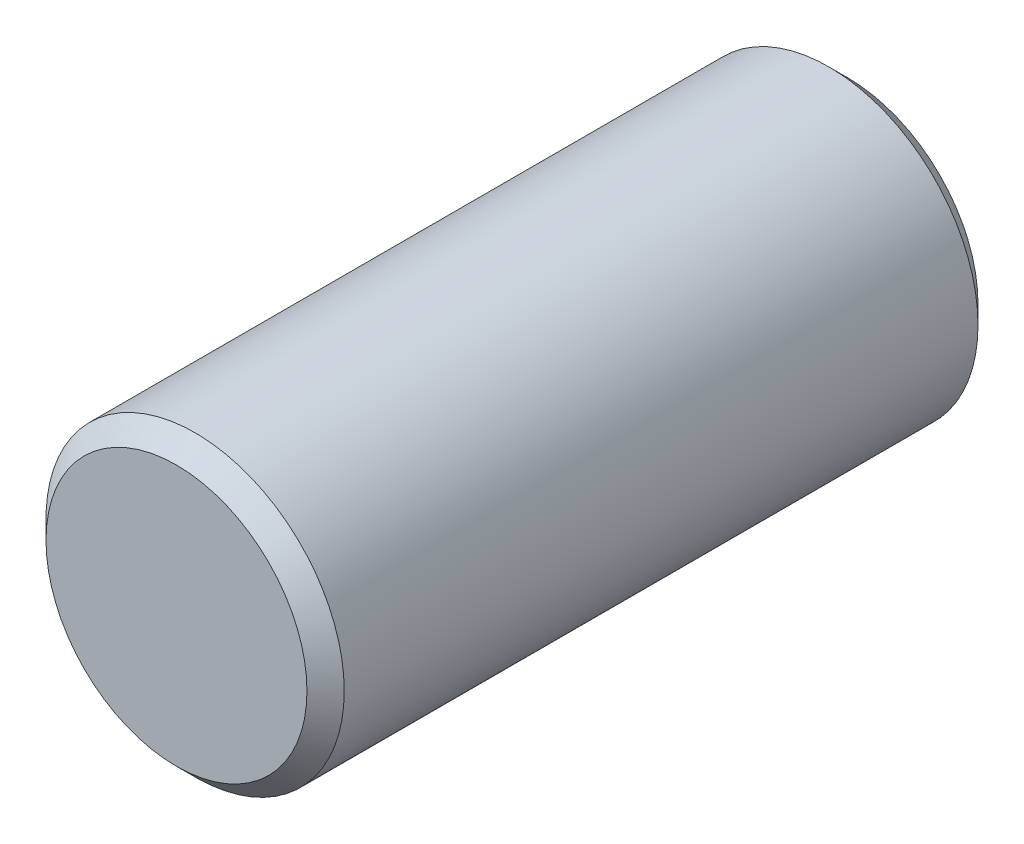
SolidWorks part; units mm, degrees
ref_plane "Piano frontale" through (0, 0, 0) normal (0, 0, 1) x (1, 0, 0)
ref_plane "Piano superiore" through (0, 0, 0) normal (0, 1, 0) x (1, 0, 0)
ref_plane "Piano destro" through (0, 0, 0) normal (1, 0, 0) x (0, 0, -1)
sketch "Schizzo1" plane through (0, 0, 0) normal (0, 0, 1) x (1, 0, 0)
  circle A0 centre (0, 0) radius 4
  dimension "D1" = 8
extrude "Estrusione-Estrusione1" add sketch "Schizzo1" along normal blind 18
chamfer "Smusso1" distance 0.5 angle 45 2 edges at (4, 0, 0) (4, 0, 18)
